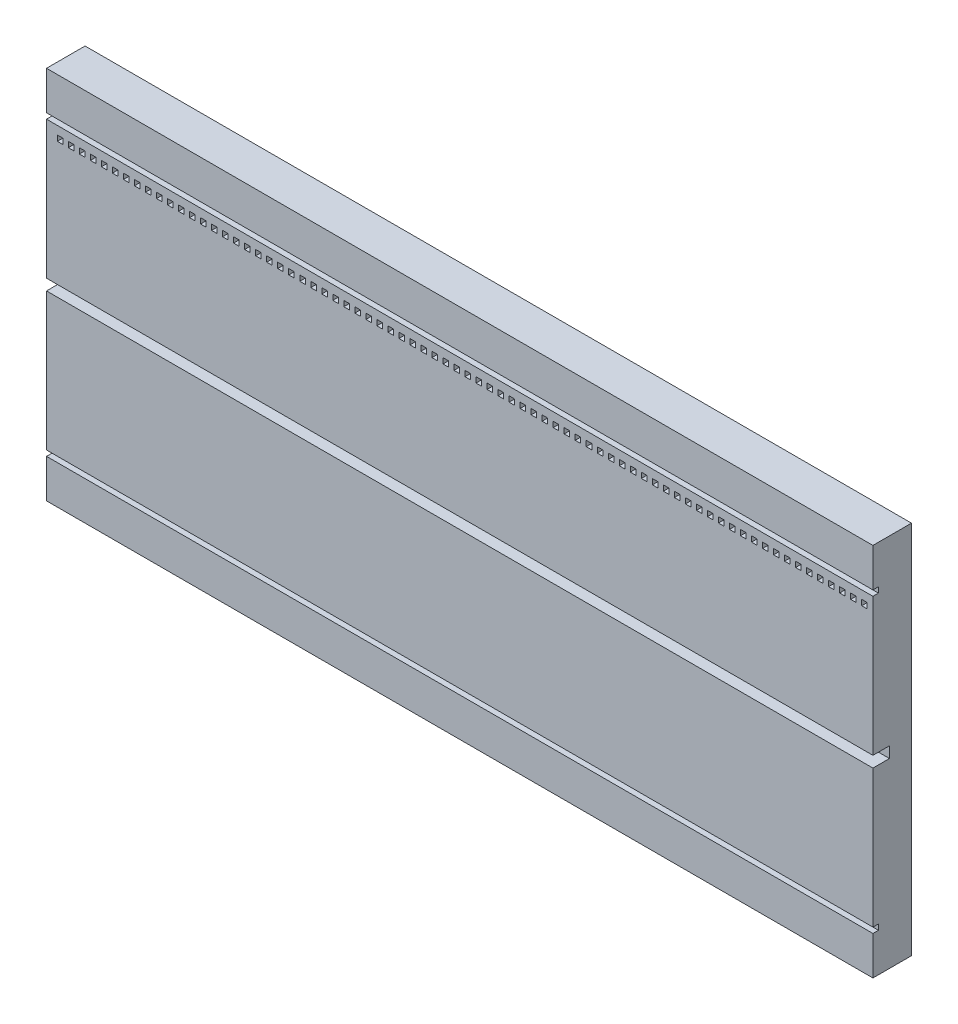
SolidWorks part; units mm, degrees
ref_plane "Ön Düzlem" through (0, 0, 0) normal (0, 0, 1) x (1, 0, 0)
ref_plane "Üst Düzlem" through (0, 0, 0) normal (0, 1, 0) x (1, 0, 0)
ref_plane "Sağ Düzlem" through (0, 0, 0) normal (1, 0, 0) x (0, 0, -1)
sketch "Çizim1" plane through (0, 0, 0) normal (0, 0, 1) x (1, 0, 0)
  line L1 (-75, 34) -> (75, 34)
  line L2 (-75, 34) -> (-75, -34)
  line L3 (-75, -34) -> (75, -34)
  line L4 (75, 34) -> (75, -34)
  line L5 (-75, 34) -> (75, -34) construction
  line L6 (-75, -34) -> (75, 34) construction
  point P0 (0, 0)
  dimension "D1" = 150
  dimension "D2" = 68
extrude "Yükseklik-Ekstrüzyon1" add sketch "Çizim1" along normal blind 7
sketch "Çizim2" plane through (0, 0, 7) normal (0, 0, 1) x (1, 0, 0)
  line L0 (-75, 27) -> (75, 27)
  line L1 (-75, 34) -> (-75, -34) construction
  line L2 (75, -34) -> (75, 34) construction
  line L3 (-75, 26) -> (75, 26)
  line L4 (75, 34) -> (-75, 34) construction
  line L5 (-75, 27) -> (-75, 26)
  line L6 (75, 27) -> (75, 26)
  dimension "D1" = 7
  dimension "D2" = 1
extrude "Kes-Ekstrüzyon1" cut sketch "Çizim2" against normal blind 1
sketch "Çizim3" plane through (0, 0, 7) normal (0, 0, 1) x (1, 0, 0)
  line L0 (-75, -26) -> (75, -26)
  line L1 (-75, 26) -> (-75, -34) construction
  line L2 (75, -34) -> (75, 26) construction
  line L3 (-75, -27) -> (75, -27)
  line L4 (-75, -34) -> (75, -34) construction
  line L5 (-75, -26) -> (-75, -27)
  line L6 (75, -26) -> (75, -27)
  dimension "D1" = 7
  dimension "D2" = 1
extrude "Kes-Ekstrüzyon2" cut sketch "Çizim3" against normal blind 1
sketch "Çizim4" plane through (0, 0, 7) normal (0, 0, 1) x (1, 0, 0)
  line L0 (-75, 1) -> (75, 1)
  line L1 (-75, 26) -> (-75, -26) construction
  line L2 (75, -26) -> (75, 26) construction
  line L3 (-75, -1) -> (75, -1)
  line L6 (75, -26) -> (-75, -26) construction
  line L8 (75, 1) -> (75, -1)
  line L9 (-75, 1) -> (-75, -1)
  dimension "D1" = 25
  dimension "D2" = 2
extrude "Kes-Ekstrüzyon5" cut sketch "Çizim4" against normal blind 3
sketch "Çizim5" plane through (0, 0, 7) normal (0, 0, 1) x (1, 0, 0)
  line L0 (75, 24) -> (-75, 24) construction
  line L1 (75, 1) -> (75, 26) construction
  line L2 (-75, 26) -> (-75, 1) construction
  line L3 (75, 22) -> (-75, 22) construction
  line L4 (75, 18.7033) -> (-75, 18.7033) construction
  line L5 (-75, 26) -> (75, 26) construction
  line L6 (72.9659, 24.5) -> (73.9659, 24.5)
  line L7 (72.9659, 24.5) -> (72.9659, 23.5)
  line L8 (72.9659, 23.5) -> (73.9659, 23.5)
  line L9 (73.9659, 24.5) -> (73.9659, 23.5)
  line L10 (72.9659, 24.5) -> (73.9659, 23.5) construction
  line L11 (72.9659, 23.5) -> (73.9659, 24.5) construction
  line L12 (70.9659, 24.5) -> (71.9659, 24.5)
  line L13 (71.9659, 24.5) -> (71.9659, 23.5)
  line L14 (70.9659, 23.5) -> (71.9659, 23.5)
  line L15 (70.9659, 24.5) -> (70.9659, 23.5)
  line L16 (68.9659, 24.5) -> (69.9659, 24.5)
  line L17 (69.9659, 24.5) -> (69.9659, 23.5)
  line L18 (68.9659, 23.5) -> (69.9659, 23.5)
  line L19 (68.9659, 24.5) -> (68.9659, 23.5)
  line L20 (66.9659, 24.5) -> (67.9659, 24.5)
  line L21 (67.9659, 24.5) -> (67.9659, 23.5)
  line L22 (66.9659, 23.5) -> (67.9659, 23.5)
  line L23 (66.9659, 24.5) -> (66.9659, 23.5)
  line L24 (64.9659, 24.5) -> (65.9659, 24.5)
  line L25 (65.9659, 24.5) -> (65.9659, 23.5)
  line L26 (64.9659, 23.5) -> (65.9659, 23.5)
  line L27 (64.9659, 24.5) -> (64.9659, 23.5)
  line L28 (62.9659, 24.5) -> (63.9659, 24.5)
  line L29 (63.9659, 24.5) -> (63.9659, 23.5)
  line L30 (62.9659, 23.5) -> (63.9659, 23.5)
  line L31 (62.9659, 24.5) -> (62.9659, 23.5)
  line L32 (60.9659, 24.5) -> (61.9659, 24.5)
  line L33 (61.9659, 24.5) -> (61.9659, 23.5)
  line L34 (60.9659, 23.5) -> (61.9659, 23.5)
  line L35 (60.9659, 24.5) -> (60.9659, 23.5)
  line L36 (58.9659, 24.5) -> (59.9659, 24.5)
  line L37 (59.9659, 24.5) -> (59.9659, 23.5)
  line L38 (58.9659, 23.5) -> (59.9659, 23.5)
  line L39 (58.9659, 24.5) -> (58.9659, 23.5)
  line L40 (56.9659, 24.5) -> (57.9659, 24.5)
  line L41 (57.9659, 24.5) -> (57.9659, 23.5)
  line L42 (56.9659, 23.5) -> (57.9659, 23.5)
  line L43 (56.9659, 24.5) -> (56.9659, 23.5)
  line L44 (54.9659, 24.5) -> (55.9659, 24.5)
  line L45 (55.9659, 24.5) -> (55.9659, 23.5)
  line L46 (54.9659, 23.5) -> (55.9659, 23.5)
  line L47 (54.9659, 24.5) -> (54.9659, 23.5)
  line L48 (52.9659, 24.5) -> (53.9659, 24.5)
  line L49 (53.9659, 24.5) -> (53.9659, 23.5)
  line L50 (52.9659, 23.5) -> (53.9659, 23.5)
  line L51 (52.9659, 24.5) -> (52.9659, 23.5)
  line L52 (50.9659, 24.5) -> (51.9659, 24.5)
  line L53 (51.9659, 24.5) -> (51.9659, 23.5)
  line L54 (50.9659, 23.5) -> (51.9659, 23.5)
  line L55 (50.9659, 24.5) -> (50.9659, 23.5)
  line L56 (48.9659, 24.5) -> (49.9659, 24.5)
  line L57 (49.9659, 24.5) -> (49.9659, 23.5)
  line L58 (48.9659, 23.5) -> (49.9659, 23.5)
  line L59 (48.9659, 24.5) -> (48.9659, 23.5)
  line L60 (46.9659, 24.5) -> (47.9659, 24.5)
  line L61 (47.9659, 24.5) -> (47.9659, 23.5)
  line L62 (46.9659, 23.5) -> (47.9659, 23.5)
  line L63 (46.9659, 24.5) -> (46.9659, 23.5)
  line L64 (44.9659, 24.5) -> (45.9659, 24.5)
  line L65 (45.9659, 24.5) -> (45.9659, 23.5)
  line L66 (44.9659, 23.5) -> (45.9659, 23.5)
  line L67 (44.9659, 24.5) -> (44.9659, 23.5)
  line L68 (42.9659, 24.5) -> (43.9659, 24.5)
  line L69 (43.9659, 24.5) -> (43.9659, 23.5)
  line L70 (42.9659, 23.5) -> (43.9659, 23.5)
  line L71 (42.9659, 24.5) -> (42.9659, 23.5)
  line L72 (40.9659, 24.5) -> (41.9659, 24.5)
  line L73 (41.9659, 24.5) -> (41.9659, 23.5)
  line L74 (40.9659, 23.5) -> (41.9659, 23.5)
  line L75 (40.9659, 24.5) -> (40.9659, 23.5)
  line L76 (38.9659, 24.5) -> (39.9659, 24.5)
  line L77 (39.9659, 24.5) -> (39.9659, 23.5)
  line L78 (38.9659, 23.5) -> (39.9659, 23.5)
  line L79 (38.9659, 24.5) -> (38.9659, 23.5)
  line L80 (36.9659, 24.5) -> (37.9659, 24.5)
  line L81 (37.9659, 24.5) -> (37.9659, 23.5)
  line L82 (36.9659, 23.5) -> (37.9659, 23.5)
  line L83 (36.9659, 24.5) -> (36.9659, 23.5)
  line L84 (34.9659, 24.5) -> (35.9659, 24.5)
  line L85 (35.9659, 24.5) -> (35.9659, 23.5)
  line L86 (34.9659, 23.5) -> (35.9659, 23.5)
  line L87 (34.9659, 24.5) -> (34.9659, 23.5)
  line L88 (32.9659, 24.5) -> (33.9659, 24.5)
  line L89 (33.9659, 24.5) -> (33.9659, 23.5)
  line L90 (32.9659, 23.5) -> (33.9659, 23.5)
  line L91 (32.9659, 24.5) -> (32.9659, 23.5)
  line L92 (30.9659, 24.5) -> (31.9659, 24.5)
  line L93 (31.9659, 24.5) -> (31.9659, 23.5)
  line L94 (30.9659, 23.5) -> (31.9659, 23.5)
  line L95 (30.9659, 24.5) -> (30.9659, 23.5)
  line L96 (28.9659, 24.5) -> (29.9659, 24.5)
  line L97 (29.9659, 24.5) -> (29.9659, 23.5)
  line L98 (28.9659, 23.5) -> (29.9659, 23.5)
  line L99 (28.9659, 24.5) -> (28.9659, 23.5)
  line L100 (26.9659, 24.5) -> (27.9659, 24.5)
  line L101 (27.9659, 24.5) -> (27.9659, 23.5)
  line L102 (26.9659, 23.5) -> (27.9659, 23.5)
  line L103 (26.9659, 24.5) -> (26.9659, 23.5)
  line L104 (24.9659, 24.5) -> (25.9659, 24.5)
  line L105 (25.9659, 24.5) -> (25.9659, 23.5)
  line L106 (24.9659, 23.5) -> (25.9659, 23.5)
  line L107 (24.9659, 24.5) -> (24.9659, 23.5)
  line L108 (22.9659, 24.5) -> (23.9659, 24.5)
  line L109 (23.9659, 24.5) -> (23.9659, 23.5)
  line L110 (22.9659, 23.5) -> (23.9659, 23.5)
  line L111 (22.9659, 24.5) -> (22.9659, 23.5)
  line L112 (20.9659, 24.5) -> (21.9659, 24.5)
  line L113 (21.9659, 24.5) -> (21.9659, 23.5)
  line L114 (20.9659, 23.5) -> (21.9659, 23.5)
  line L115 (20.9659, 24.5) -> (20.9659, 23.5)
  line L116 (18.9659, 24.5) -> (19.9659, 24.5)
  line L117 (19.9659, 24.5) -> (19.9659, 23.5)
  line L118 (18.9659, 23.5) -> (19.9659, 23.5)
  line L119 (18.9659, 24.5) -> (18.9659, 23.5)
  line L120 (16.9659, 24.5) -> (17.9659, 24.5)
  line L121 (17.9659, 24.5) -> (17.9659, 23.5)
  line L122 (16.9659, 23.5) -> (17.9659, 23.5)
  line L123 (16.9659, 24.5) -> (16.9659, 23.5)
  line L124 (14.9659, 24.5) -> (15.9659, 24.5)
  line L125 (15.9659, 24.5) -> (15.9659, 23.5)
  line L126 (14.9659, 23.5) -> (15.9659, 23.5)
  line L127 (14.9659, 24.5) -> (14.9659, 23.5)
  line L128 (12.9659, 24.5) -> (13.9659, 24.5)
  line L129 (13.9659, 24.5) -> (13.9659, 23.5)
  line L130 (12.9659, 23.5) -> (13.9659, 23.5)
  line L131 (12.9659, 24.5) -> (12.9659, 23.5)
  line L132 (10.9659, 24.5) -> (11.9659, 24.5)
  line L133 (11.9659, 24.5) -> (11.9659, 23.5)
  line L134 (10.9659, 23.5) -> (11.9659, 23.5)
  line L135 (10.9659, 24.5) -> (10.9659, 23.5)
  line L136 (8.9659, 24.5) -> (9.9659, 24.5)
  line L137 (9.9659, 24.5) -> (9.9659, 23.5)
  line L138 (8.9659, 23.5) -> (9.9659, 23.5)
  line L139 (8.9659, 24.5) -> (8.9659, 23.5)
  line L140 (6.9659, 24.5) -> (7.9659, 24.5)
  line L141 (7.9659, 24.5) -> (7.9659, 23.5)
  line L142 (6.9659, 23.5) -> (7.9659, 23.5)
  line L143 (6.9659, 24.5) -> (6.9659, 23.5)
  line L144 (4.9659, 24.5) -> (5.9659, 24.5)
  line L145 (5.9659, 24.5) -> (5.9659, 23.5)
  line L146 (4.9659, 23.5) -> (5.9659, 23.5)
  line L147 (4.9659, 24.5) -> (4.9659, 23.5)
  line L148 (2.9659, 24.5) -> (3.9659, 24.5)
  line L149 (3.9659, 24.5) -> (3.9659, 23.5)
  line L150 (2.9659, 23.5) -> (3.9659, 23.5)
  line L151 (2.9659, 24.5) -> (2.9659, 23.5)
  line L152 (0.9659, 24.5) -> (1.9659, 24.5)
  line L153 (1.9659, 24.5) -> (1.9659, 23.5)
  line L154 (0.9659, 23.5) -> (1.9659, 23.5)
  line L155 (0.9659, 24.5) -> (0.9659, 23.5)
  line L156 (-1.0341, 24.5) -> (-0.0341, 24.5)
  line L157 (-0.0341, 24.5) -> (-0.0341, 23.5)
  line L158 (-1.0341, 23.5) -> (-0.0341, 23.5)
  line L159 (-1.0341, 24.5) -> (-1.0341, 23.5)
  line L160 (-3.0341, 24.5) -> (-2.0341, 24.5)
  line L161 (-2.0341, 24.5) -> (-2.0341, 23.5)
  line L162 (-3.0341, 23.5) -> (-2.0341, 23.5)
  line L163 (-3.0341, 24.5) -> (-3.0341, 23.5)
  line L164 (-5.0341, 24.5) -> (-4.0341, 24.5)
  line L165 (-4.0341, 24.5) -> (-4.0341, 23.5)
  line L166 (-5.0341, 23.5) -> (-4.0341, 23.5)
  line L167 (-5.0341, 24.5) -> (-5.0341, 23.5)
  line L168 (-7.0341, 24.5) -> (-6.0341, 24.5)
  line L169 (-6.0341, 24.5) -> (-6.0341, 23.5)
  line L170 (-7.0341, 23.5) -> (-6.0341, 23.5)
  line L171 (-7.0341, 24.5) -> (-7.0341, 23.5)
  line L172 (-9.0341, 24.5) -> (-8.0341, 24.5)
  line L173 (-8.0341, 24.5) -> (-8.0341, 23.5)
  line L174 (-9.0341, 23.5) -> (-8.0341, 23.5)
  line L175 (-9.0341, 24.5) -> (-9.0341, 23.5)
  line L176 (-11.0341, 24.5) -> (-10.0341, 24.5)
  line L177 (-10.0341, 24.5) -> (-10.0341, 23.5)
  line L178 (-11.0341, 23.5) -> (-10.0341, 23.5)
  line L179 (-11.0341, 24.5) -> (-11.0341, 23.5)
  line L180 (-13.0341, 24.5) -> (-12.0341, 24.5)
  line L181 (-12.0341, 24.5) -> (-12.0341, 23.5)
  line L182 (-13.0341, 23.5) -> (-12.0341, 23.5)
  line L183 (-13.0341, 24.5) -> (-13.0341, 23.5)
  line L184 (-15.0341, 24.5) -> (-14.0341, 24.5)
  line L185 (-14.0341, 24.5) -> (-14.0341, 23.5)
  line L186 (-15.0341, 23.5) -> (-14.0341, 23.5)
  line L187 (-15.0341, 24.5) -> (-15.0341, 23.5)
  line L188 (-17.0341, 24.5) -> (-16.0341, 24.5)
  line L189 (-16.0341, 24.5) -> (-16.0341, 23.5)
  line L190 (-17.0341, 23.5) -> (-16.0341, 23.5)
  line L191 (-17.0341, 24.5) -> (-17.0341, 23.5)
  line L192 (-19.0341, 24.5) -> (-18.0341, 24.5)
  line L193 (-18.0341, 24.5) -> (-18.0341, 23.5)
  line L194 (-19.0341, 23.5) -> (-18.0341, 23.5)
  line L195 (-19.0341, 24.5) -> (-19.0341, 23.5)
  line L196 (-21.0341, 24.5) -> (-20.0341, 24.5)
  line L197 (-20.0341, 24.5) -> (-20.0341, 23.5)
  line L198 (-21.0341, 23.5) -> (-20.0341, 23.5)
  line L199 (-21.0341, 24.5) -> (-21.0341, 23.5)
  line L200 (-23.0341, 24.5) -> (-22.0341, 24.5)
  line L201 (-22.0341, 24.5) -> (-22.0341, 23.5)
  line L202 (-23.0341, 23.5) -> (-22.0341, 23.5)
  line L203 (-23.0341, 24.5) -> (-23.0341, 23.5)
  line L204 (-25.0341, 24.5) -> (-24.0341, 24.5)
  line L205 (-24.0341, 24.5) -> (-24.0341, 23.5)
  line L206 (-25.0341, 23.5) -> (-24.0341, 23.5)
  line L207 (-25.0341, 24.5) -> (-25.0341, 23.5)
  line L208 (-27.0341, 24.5) -> (-26.0341, 24.5)
  line L209 (-26.0341, 24.5) -> (-26.0341, 23.5)
  line L210 (-27.0341, 23.5) -> (-26.0341, 23.5)
  line L211 (-27.0341, 24.5) -> (-27.0341, 23.5)
  line L212 (-29.0341, 24.5) -> (-28.0341, 24.5)
  line L213 (-28.0341, 24.5) -> (-28.0341, 23.5)
  line L214 (-29.0341, 23.5) -> (-28.0341, 23.5)
  line L215 (-29.0341, 24.5) -> (-29.0341, 23.5)
  line L216 (-31.0341, 24.5) -> (-30.0341, 24.5)
  line L217 (-30.0341, 24.5) -> (-30.0341, 23.5)
  line L218 (-31.0341, 23.5) -> (-30.0341, 23.5)
  line L219 (-31.0341, 24.5) -> (-31.0341, 23.5)
  line L220 (-33.0341, 24.5) -> (-32.0341, 24.5)
  line L221 (-32.0341, 24.5) -> (-32.0341, 23.5)
  line L222 (-33.0341, 23.5) -> (-32.0341, 23.5)
  line L223 (-33.0341, 24.5) -> (-33.0341, 23.5)
  line L224 (-35.0341, 24.5) -> (-34.0341, 24.5)
  line L225 (-34.0341, 24.5) -> (-34.0341, 23.5)
  line L226 (-35.0341, 23.5) -> (-34.0341, 23.5)
  line L227 (-35.0341, 24.5) -> (-35.0341, 23.5)
  line L228 (-37.0341, 24.5) -> (-36.0341, 24.5)
  line L229 (-36.0341, 24.5) -> (-36.0341, 23.5)
  line L230 (-37.0341, 23.5) -> (-36.0341, 23.5)
  line L231 (-37.0341, 24.5) -> (-37.0341, 23.5)
  line L232 (-39.0341, 24.5) -> (-38.0341, 24.5)
  line L233 (-38.0341, 24.5) -> (-38.0341, 23.5)
  line L234 (-39.0341, 23.5) -> (-38.0341, 23.5)
  line L235 (-39.0341, 24.5) -> (-39.0341, 23.5)
  line L236 (-41.0341, 24.5) -> (-40.0341, 24.5)
  line L237 (-40.0341, 24.5) -> (-40.0341, 23.5)
  line L238 (-41.0341, 23.5) -> (-40.0341, 23.5)
  line L239 (-41.0341, 24.5) -> (-41.0341, 23.5)
  line L240 (-43.0341, 24.5) -> (-42.0341, 24.5)
  line L241 (-42.0341, 24.5) -> (-42.0341, 23.5)
  line L242 (-43.0341, 23.5) -> (-42.0341, 23.5)
  line L243 (-43.0341, 24.5) -> (-43.0341, 23.5)
  line L244 (-45.0341, 24.5) -> (-44.0341, 24.5)
  line L245 (-44.0341, 24.5) -> (-44.0341, 23.5)
  line L246 (-45.0341, 23.5) -> (-44.0341, 23.5)
  line L247 (-45.0341, 24.5) -> (-45.0341, 23.5)
  line L248 (-47.0341, 24.5) -> (-46.0341, 24.5)
  line L249 (-46.0341, 24.5) -> (-46.0341, 23.5)
  line L250 (-47.0341, 23.5) -> (-46.0341, 23.5)
  line L251 (-47.0341, 24.5) -> (-47.0341, 23.5)
  line L252 (-49.0341, 24.5) -> (-48.0341, 24.5)
  line L253 (-48.0341, 24.5) -> (-48.0341, 23.5)
  line L254 (-49.0341, 23.5) -> (-48.0341, 23.5)
  line L255 (-49.0341, 24.5) -> (-49.0341, 23.5)
  line L256 (-51.0341, 24.5) -> (-50.0341, 24.5)
  line L257 (-50.0341, 24.5) -> (-50.0341, 23.5)
  line L258 (-51.0341, 23.5) -> (-50.0341, 23.5)
  line L259 (-51.0341, 24.5) -> (-51.0341, 23.5)
  line L260 (-53.0341, 24.5) -> (-52.0341, 24.5)
  line L261 (-52.0341, 24.5) -> (-52.0341, 23.5)
  line L262 (-53.0341, 23.5) -> (-52.0341, 23.5)
  line L263 (-53.0341, 24.5) -> (-53.0341, 23.5)
  line L264 (-55.0341, 24.5) -> (-54.0341, 24.5)
  line L265 (-54.0341, 24.5) -> (-54.0341, 23.5)
  line L266 (-55.0341, 23.5) -> (-54.0341, 23.5)
  line L267 (-55.0341, 24.5) -> (-55.0341, 23.5)
  line L268 (-57.0341, 24.5) -> (-56.0341, 24.5)
  line L269 (-56.0341, 24.5) -> (-56.0341, 23.5)
  line L270 (-57.0341, 23.5) -> (-56.0341, 23.5)
  line L271 (-57.0341, 24.5) -> (-57.0341, 23.5)
  line L272 (-59.0341, 24.5) -> (-58.0341, 24.5)
  line L273 (-58.0341, 24.5) -> (-58.0341, 23.5)
  line L274 (-59.0341, 23.5) -> (-58.0341, 23.5)
  line L275 (-59.0341, 24.5) -> (-59.0341, 23.5)
  line L276 (-61.0341, 24.5) -> (-60.0341, 24.5)
  line L277 (-60.0341, 24.5) -> (-60.0341, 23.5)
  line L278 (-61.0341, 23.5) -> (-60.0341, 23.5)
  line L279 (-61.0341, 24.5) -> (-61.0341, 23.5)
  line L280 (-63.0341, 24.5) -> (-62.0341, 24.5)
  line L281 (-62.0341, 24.5) -> (-62.0341, 23.5)
  line L282 (-63.0341, 23.5) -> (-62.0341, 23.5)
  line L283 (-63.0341, 24.5) -> (-63.0341, 23.5)
  line L284 (-65.0341, 24.5) -> (-64.0341, 24.5)
  line L285 (-64.0341, 24.5) -> (-64.0341, 23.5)
  line L286 (-65.0341, 23.5) -> (-64.0341, 23.5)
  line L287 (-65.0341, 24.5) -> (-65.0341, 23.5)
  line L288 (-67.0341, 24.5) -> (-66.0341, 24.5)
  line L289 (-66.0341, 24.5) -> (-66.0341, 23.5)
  line L290 (-67.0341, 23.5) -> (-66.0341, 23.5)
  line L291 (-67.0341, 24.5) -> (-67.0341, 23.5)
  line L292 (-69.0341, 24.5) -> (-68.0341, 24.5)
  line L293 (-68.0341, 24.5) -> (-68.0341, 23.5)
  line L294 (-69.0341, 23.5) -> (-68.0341, 23.5)
  line L295 (-69.0341, 24.5) -> (-69.0341, 23.5)
  line L296 (-71.0341, 24.5) -> (-70.0341, 24.5)
  line L297 (-70.0341, 24.5) -> (-70.0341, 23.5)
  line L298 (-71.0341, 23.5) -> (-70.0341, 23.5)
  line L299 (-71.0341, 24.5) -> (-71.0341, 23.5)
  line L300 (-73.0341, 24.5) -> (-72.0341, 24.5)
  line L301 (-72.0341, 24.5) -> (-72.0341, 23.5)
  line L302 (-73.0341, 23.5) -> (-72.0341, 23.5)
  line L303 (-73.0341, 24.5) -> (-73.0341, 23.5)
  point P10 (73.4659, 24)
  dimension "D1" = 1
  dimension "D2" = 1
  dimension "D3" = 2
  dimension "D4" = 2
  dimension "D5" = 74
extrude "Kes-Ekstrüzyon6" cut sketch "Çizim5" against normal blind 1
